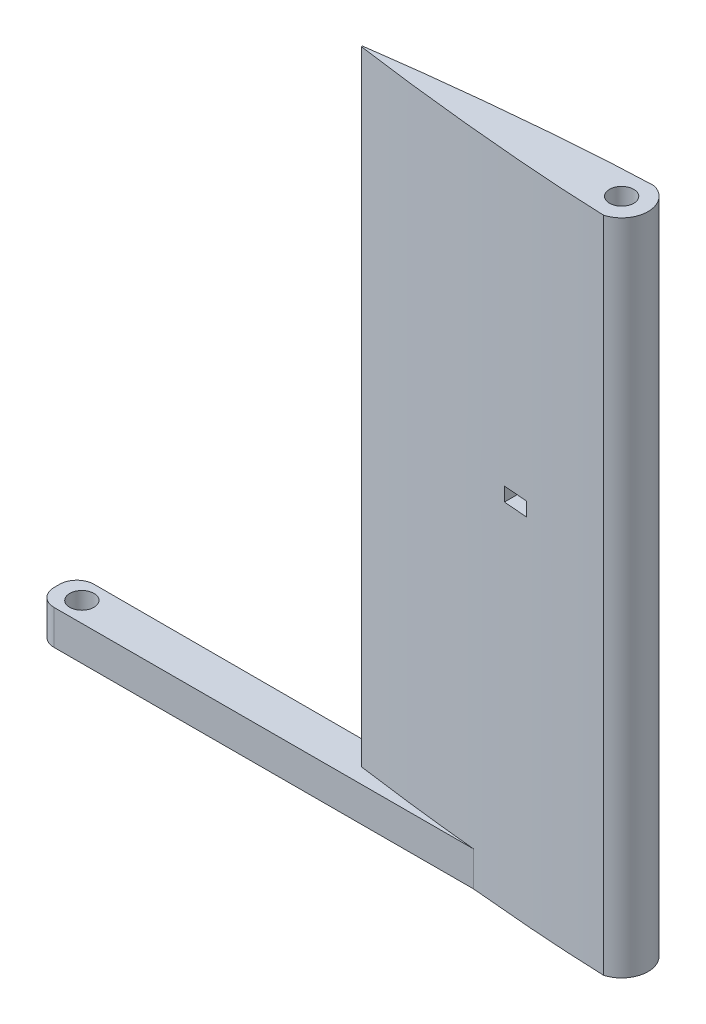
SolidWorks part; units mm, degrees
ref_plane "Front Plane" through (0, 0, 0) normal (0, 0, 1) x (1, 0, 0)
ref_plane "Top Plane" through (0, 0, 0) normal (0, 1, 0) x (1, 0, 0)
ref_plane "Right Plane" through (0, 0, 0) normal (1, 0, 0) x (0, 0, -1)
sketch "Sketch1" plane through (0, 0, 0) normal (0, 1, 0) x (1, 0, 0)
  line L0 (-22.3, 0.4217) -> (-22.3, 0.5818)
  circle A0 centre (15.7861, 0.5017) radius 1.778
  arc A1 (16.8691, -3.2222) -> (16.8691, 4.2257) centre (15.7861, 0.5017) ccw
  spline S0 degree 3 poles (16.8691, -3.2222) (16.5339, -3.2111) (15.1399, -3.1609) (12.6662, -3.0536) (9.4701, -2.8665) (6.2739, -2.6478) (3.0989, -2.3998) (-0.0761, -2.1269) (-3.2511, -1.8284) (-6.4261, -1.5082) (-9.6012, -1.1671) (-12.7763, -0.8056) (-15.9514, -0.4209) (-19.1269, -0.016) (-21.2419, 0.2758) (-22.3, 0.4217) knots 0.697451 0.697451 0.697451 0.697451 0.705187 0.72962 0.754558 0.779024 0.803506 0.828005 0.852521 0.877054 0.901603 0.92617 0.950757 0.975366 1 1 1 1
  spline S1 degree 3 poles (-22.3, 0.5818) (-21.2419, 0.7277) (-19.1269, 1.0194) (-15.9514, 1.4244) (-12.7763, 1.8091) (-9.6012, 2.1706) (-6.4261, 2.5117) (-3.2511, 2.8319) (-0.0761, 3.1303) (3.0989, 3.4033) (6.2739, 3.6513) (9.4701, 3.87) (12.6662, 4.0571) (15.1399, 4.1643) (16.5339, 4.2146) (16.8691, 4.2257) knots 0 0 0 0 0.024634 0.049243 0.07383 0.098397 0.122946 0.147479 0.171995 0.196494 0.220976 0.245442 0.27038 0.294813 0.302549 0.302549 0.302549 0.302549
extrude "Boss-Extrude1" add sketch "Sketch1" along normal blind 96.52
ref_plane "Plane1" through (0, 0, 2.54) normal (0, 0, 1) x (1, 0, 0)
sketch "Sketch2" plane through (0, 0, 2.54) normal (0, 0, 1) x (1, 0, 0)
  line L1 (6.9453, 51.8555) -> (1.3573, 51.8555)
  line L2 (6.9453, 51.8555) -> (6.9453, 53.8875)
  line L3 (6.9453, 53.8875) -> (1.3573, 53.8875)
  line L4 (1.3573, 51.8555) -> (1.3573, 53.8875)
  line L5 (6.9453, 51.8555) -> (1.3573, 53.8875) construction
  line L6 (6.9453, 53.8875) -> (1.3573, 51.8555) construction
  point P0 (4.1513, 52.8715)
  dimension "D1" = 5.588
  dimension "D2" = 2.032
extrude "Cut-Extrude1" cut sketch "Sketch2" against normal blind 3.048
ref_plane "Plane2" through (0, 0, 0) normal (0, -1, 0) x (-1, 0, 0)
sketch "Sketch3" plane through (0, 0, 0) normal (0, -1, 0) x (-1, 0, 0)
  line L0 (16.7928, 1.3157) -> (16.7928, 3.9954)
  line L1 (16.7928, 3.9954) -> (67.5928, 3.9954)
  line L4 (22.3, 0.5818) -> (22.3, 0.4217) construction
  line L5 (22.3, 0.5818) -> (22.3, 0.4217)
  line L6 (22.3, 0.5818) -> (67.5928, 0.5818)
  line L7 (67.5928, 0.5818) -> (67.5928, 3.9954)
  line L8 (16.7928, 3.9954) -> (6.0142, 2.5509)
  line L9 (67.5928, 0.5818) -> (67.5928, -1.8793)
  line L10 (67.5928, -1.8793) -> (3.6307, -1.7877)
  spline S0 degree 3 poles (-261.0186, -4984.1017) (-176.3426, -22.87) (-94.2467, 7.5933) (-12.6662, 4.0571) (-9.4701, 3.87) (-6.2739, 3.6513) (-3.0989, 3.4033) (0.0761, 3.1303) (3.2511, 2.8319) (6.4261, 2.5117) (9.6012, 2.1706) (12.7763, 1.8091) (15.9514, 1.4244) (121.8791, -12.0849) (219.6608, -78.5015) (990.0712, 4896.375) knots -1.826179 -1.826179 -1.826179 -1.826179 0.007736 0.032168 0.057107 0.081573 0.106055 0.130554 0.15507 0.179603 0.204152 0.228719 0.253306 0.277915 2.691534 2.691534 2.691534 2.691534 only from (-16.8691, 4.2257) to (22.3, 0.5818) construction
  spline S1 degree 3 poles (10.6504, 2.05) (11.3588, 1.9701) (13.1261, 1.7667) (15.9514, 1.4244) (19.1269, 1.0194) (21.2419, 0.7277) (22.3, 0.5818) knots 0.212277 0.212277 0.212277 0.212277 0.228719 0.253306 0.277915 0.302549 0.302549 0.302549 0.302549
  spline S2 degree 3 poles (-16.8691, 4.2257) (-16.5339, 4.2146) (-15.1399, 4.1643) (-12.6662, 4.0571) (-9.4701, 3.87) (-6.2739, 3.6513) (-3.0989, 3.4033) (0.0761, 3.1303) (3.2511, 2.8319) (6.4261, 2.5117) (9.6012, 2.1706) (12.7763, 1.8091) (15.9514, 1.4244) (19.1269, 1.0194) (21.2419, 0.7277) (22.3, 0.5818) knots 0 0 0 0 0.007736 0.032168 0.057107 0.081573 0.106055 0.130554 0.15507 0.179603 0.204152 0.228719 0.253306 0.277915 0.302549 0.302549 0.302549 0.302549
  spline S3 degree 3 poles (676.853, -2920.315) (189.3753, 60.3062) (105.7287, 11.0287) (15.9514, -0.4209) (12.7763, -0.8056) (9.6012, -1.1671) (6.4261, -1.5082) (3.2511, -1.8284) (0.0761, -2.1269) (-3.0989, -2.3998) (-6.2739, -2.6478) (-9.4701, -2.8665) (-12.6662, -3.0536) (-81.7118, -6.0465) (-150.8145, 15.2097) (-221.2013, 2985.7177) knots -1.316038 -1.316038 -1.316038 -1.316038 0.722085 0.746694 0.771281 0.795848 0.820397 0.84493 0.869446 0.893945 0.918427 0.942893 0.967832 0.992264 2.536811 2.536811 2.536811 2.536811 only from (22.3, 0.4217) to (-16.8691, -3.2222) construction
  spline S4 degree 3 poles (22.3, 0.4217) (21.2419, 0.2758) (19.1269, -0.016) (15.9514, -0.4209) (12.7763, -0.8056) (9.6012, -1.1671) (6.4261, -1.5082) (3.2511, -1.8284) (0.0761, -2.1269) (-3.0989, -2.3998) (-6.2739, -2.6478) (-9.4701, -2.8665) (-12.6662, -3.0536) (-15.1399, -3.1609) (-16.5339, -3.2111) (-16.8691, -3.2222) knots 0.697451 0.697451 0.697451 0.697451 0.722085 0.746694 0.771281 0.795848 0.820397 0.84493 0.869446 0.893945 0.918427 0.942893 0.967832 0.992264 1 1 1 1
  dimension "D1" = 50.8
extrude "Boss-Extrude4" add sketch "Sketch3" against normal blind 5.08 contours L8 S2 S1 L0 | L0 S1 L6 L7 L1 | L5 S4 L10 L9 L6
sketch "Sketch7" plane through (0, 0, 0) normal (0, -1, 0) x (-1, 0, 0)
  circle A0 centre (63.9167, 1.0581) radius 1.778
  dimension "D1" = 3.556
extrude "Cut-Extrude2" cut sketch "Sketch7" against normal blind 5.08
fillet "Fillet1" radius 2.54 2 edges at (-67.5928, 2.54, 1.8793) (-67.5928, 2.54, -3.9954)
